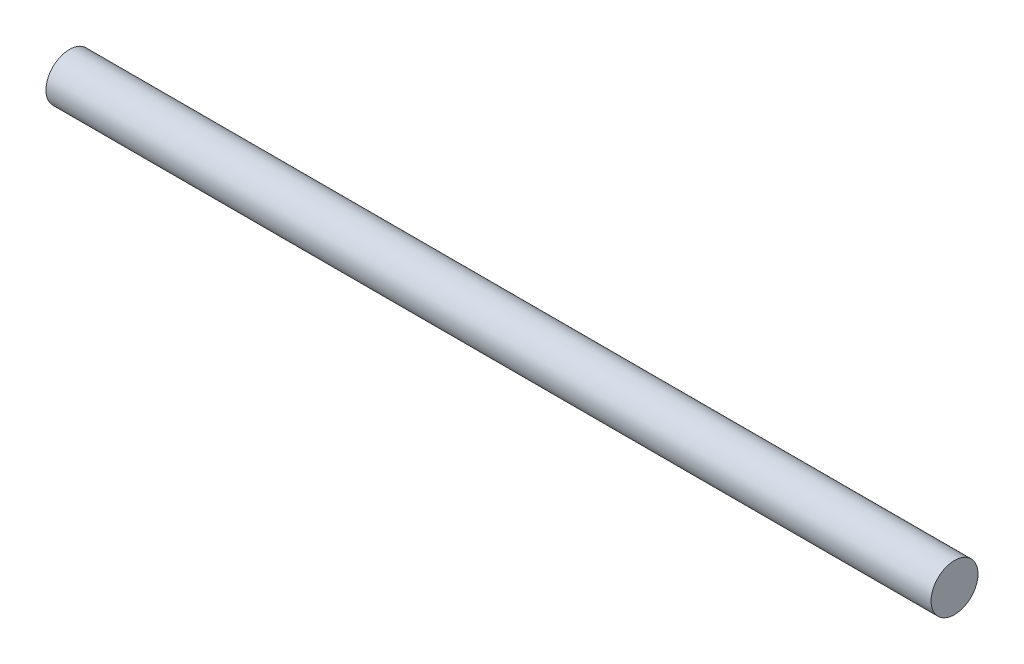
SolidWorks part; units mm, degrees
ref_plane "Front Plane" through (0, 0, 0) normal (0, 0, 1) x (1, 0, 0)
ref_plane "Top Plane" through (0, 0, 0) normal (0, 1, 0) x (1, 0, 0)
ref_plane "Right Plane" through (0, 0, 0) normal (1, 0, 0) x (0, 0, -1)
sketch "bar sketch" plane through (0, 0, 0) normal (1, 0, 0) x (0, 0, -1)
  circle A0 centre (10, 352.4) radius 9.525
extrude "bar" add sketch "bar sketch" along normal mid plane 359.04
equation "\"diffL\" = 608.8mm"
equation "\"diffW\" = 329.4mm"
equation "\"diffT\" = 2.9mm"
equation "\"chanSlotW\" = 12.9mm"
equation "\"chanSlotDepth\" = 11.13mm"
equation "\"chanFloor\" = 1.57mm"
equation "\"chanLeg\" = 12.7mm"
equation "\"lightL\" = 604.8mm"
equation "\"lightW\" = 330.2mm"
equation "\"lightH\" = 92mm"
equation "\"lightSideFlat\" = 30mm"
equation "\"lightSlopeLen\" = 38.9mm"
equation "\"lightWingDepth\" = 50.1mm"
equation "\"lightWingFlat\" = 90.2mm"
equation "\"lightChanW\" = 99.6mm"
equation "\"lightChanStand\" = 44.1mm"
equation "\"insFlangeD\" = 12.3mm"
equation "\"insFromEnd\" = 20.7mm"
equation "\"insUpSlope\" = 20.8mm"
equation "\"gaugeH\" = 10mm"
equation "\"gaugeStepLen\" = 14mm"
equation "\"gaugeStepW0\" = 13.1mm"
equation "\"gaugeStepDW\" = 0.2mm"
equation "\"gaugeSteps\" = 5mm"
equation "\"gaugeHandleLen\" = 30mm"
equation "\"gaugeHandleW\" = 24mm"
equation "\"gaugeSlot0\" = 3mm"
equation "\"gaugeSlotD\" = 0.1mm"
equation "\"gaugeSlotDepth\" = 8mm"
equation "\"gap\" = 25.4mm"
equation "\"edgeL\" = 1mm"
equation "\"edgeW\" = 0.75mm"
equation "\"proud\" = 2.5mm"
equation "\"seatClr\" = 0.15mm"
equation "\"tongueClrZ\" = 0.1mm"
equation "\"tongueClrX\" = 0.25mm"
equation "\"tongueLen\" = 30mm"
equation "\"armSide\" = 45mm"
equation "\"armEnd\" = 20mm"
equation "\"brkW\" = 26mm"
equation "\"brkT\" = 7mm"
equation "\"brkSeatClr\" = 0.3mm"
equation "\"brkScrewSpan\" = 16mm"
equation "\"pilotD\" = 4.3mm"
equation "\"pilotDepth\" = 8mm"
equation "\"screwClrD\" = 3.8mm"
equation "\"jogBelow\" = 4mm"
equation "\"padT\" = 7mm"
equation "\"padLen\" = 36mm"
equation "\"m6Clr\" = 9mm"
equation "\"m6Slot\" = 5mm"
equation "\"flangeRelD\" = 18mm"
equation "\"flangeRelDepth\" = 1.5mm"
equation "\"relLen\" = 5mm"
equation "\"relDepth\" = 3.3mm"
equation "\"knockN\" = 100mm"
equation "\"petgcfE\" = 3000mm"
equation "\"mockExtent\" = 110mm"
equation "\"relZnear\" = 9.4mm"
equation "\"relZfar\" = 23.4mm"
equation "\"headD\" = 8mm"
equation "\"headH\" = 2.5mm"
equation "\"headFromEnd\" = 6.8mm"
equation "\"headBack\" = 16.4mm"
equation "\"sideClr\" = 0.4mm"
equation "\"cornerRelR\" = 1.5mm"
equation "\"cornerRelBack\" = 0.6mm"
equation "\"endHeadH\" = 2.8mm"
equation "\"footClr\" = 1.2mm"
equation "\"footEndClr\" = 3.5mm"
equation "\"footBlockClr\" = 0.5mm"
equation "\"footBack\" = 85mm"
equation "\"footFwd\" = 10mm"
equation "\"footBraceEnd\" = 3mm"
equation "\"spacerLen\" = 60mm"
equation "\"spacerShort\" = 0.5mm"
equation "\"spacerCham\" = 0.8mm"
equation "\"spacerPerSide\" = 3mm"
equation "\"spacerPerEnd\" = 1mm"
equation "\"toolR\" = 9mm"
equation "\"visR\" = 4mm"
equation "\"edgeR\" = 1mm"
equation "\"bendOutR\" = 5mm"
equation "\"insideR\" = 2.5mm"
equation "\"footCornerR\" = 10mm"
equation "\"footFrontR\" = 8mm"
equation "\"braceKinkR\" = 12mm"
equation "\"bedCham\" = 1mm"
equation "\"bedChamSmall\" = 0.6mm"
equation "\"soleTopR\" = 2mm"
equation "\"cornerR\" = 6mm"
equation "\"rimInR\" = 1mm"
equation "\"insFlangeH\" = 1mm"
equation "\"insHoleFinishD\" = 4.5mm"
equation "\"insLen\" = 6.4mm"
equation "\"cgInset\" = 4mm"
equation "\"lampWeightN\" = 51mm"
equation "\"frameWeightN\" = 10mm"
equation "\"bumpIn\" = 8mm"
equation "\"bumpH\" = 3mm"
equation "\"legBelowFront\" = 2mm"
equation "\"lipClr\" = 0.1mm"
equation "\"revealR\" = 2mm"
equation "\"frontCham\" = 1mm"
equation "\"leanDeg\" = 5mm"
equation "\"footTailT\" = 6mm"
equation "\"v1LeanDeg\" = 4.5mm"
equation "\"toeNoseR\" = 5mm"
equation "\"petgE\" = 2000mm"
equation "\"cheekT\" = 8mm"
equation "\"handleUp\" = 50mm"
equation "\"handleZ\" = -10mm"
equation "\"gripD\" = 19.05mm"
equation "\"gripClr\" = 0.5mm"
equation "\"bossWall\" = 5mm"
equation "\"bossLen\" = 14mm"
equation "\"socketFloor\" = 4mm"
equation "\"barEndClr\" = 1mm"
equation "\"lipH\" = 4mm"
equation "\"lipDeep\" = 6mm"
